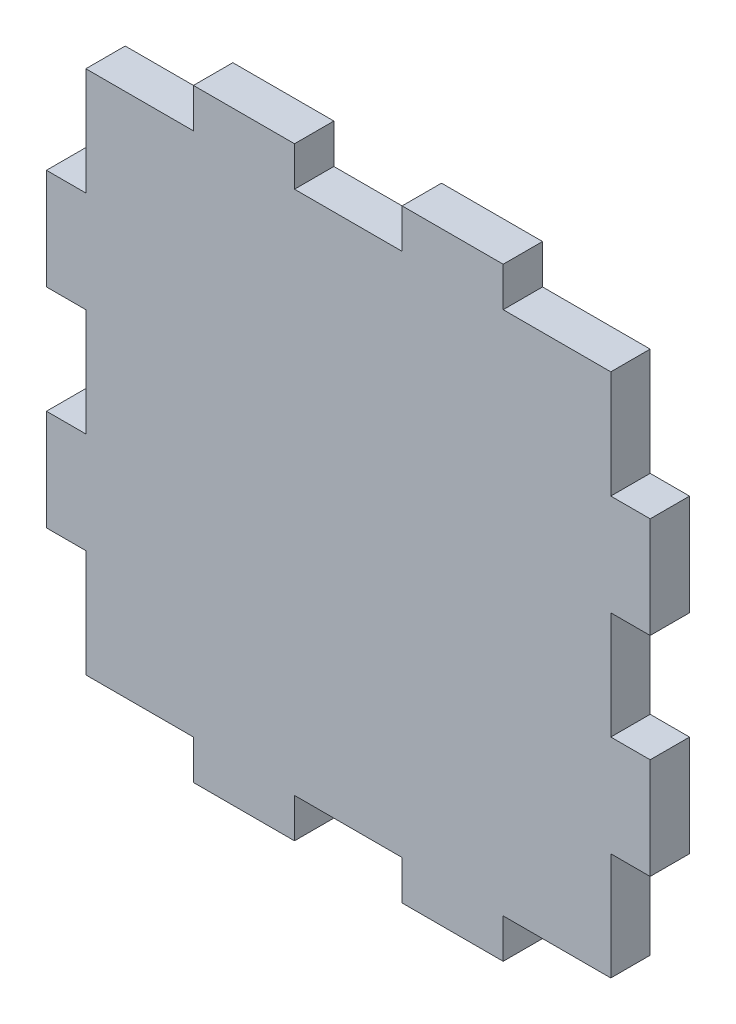
SolidWorks part; units mm, degrees
ref_plane "Alzado" through (0, 0, 0) normal (0, 0, 1) x (1, 0, 0)
ref_plane "Planta" through (0, 0, 0) normal (0, 1, 0) x (1, 0, 0)
ref_plane "Vista lateral" through (0, 0, 0) normal (1, 0, 0) x (0, 0, -1)
sketch "Croquis1" plane through (0, 0, 0) normal (0, 0, 1) x (1, 0, 0)
  line L0 (0, 0) -> (-14.3488, 0) construction
  line L1 (20, -20) -> (-20, -20)
  line L2 (20, -20) -> (20, 20)
  line L3 (20, 20) -> (-20, 20)
  line L4 (-20, -20) -> (-20, 20)
  line L5 (20, -20) -> (-20, 20) construction
  line L6 (20, 20) -> (-20, -20) construction
  line L7 (-11.8, 20) -> (-4.1, 20)
  line L8 (-11.8, 20) -> (-11.8, 23)
  line L9 (-11.8, 23) -> (-4.1, 23)
  line L10 (-4.1, 20) -> (-4.1, 23)
  line L11 (4.1, 20) -> (11.8, 20)
  line L12 (4.1, 20) -> (4.1, 23)
  line L13 (4.1, 23) -> (11.8, 23)
  line L14 (11.8, 20) -> (11.8, 23)
  line L15 (-20, 11.8) -> (-23, 11.8)
  line L16 (-20, 11.8) -> (-20, 4.1)
  line L17 (-20, 4.1) -> (-23, 4.1)
  line L18 (-23, 11.8) -> (-23, 4.1)
  line L19 (-20, -4.1) -> (-23, -4.1)
  line L20 (-20, -4.1) -> (-20, -11.8)
  line L21 (-20, -11.8) -> (-23, -11.8)
  line L22 (-23, -4.1) -> (-23, -11.8)
  line L23 (0, 0) -> (0, 14.3313) construction
  line L24 (20, -11.8) -> (23, -11.8)
  line L25 (23, -4.1) -> (23, -11.8)
  line L26 (20, -4.1) -> (23, -4.1)
  line L27 (20, -4.1) -> (20, -11.8)
  line L28 (20, 4.1) -> (23, 4.1)
  line L29 (23, 11.8) -> (23, 4.1)
  line L30 (20, 11.8) -> (23, 11.8)
  line L31 (20, 11.8) -> (20, 4.1)
  line L32 (4.1, -23) -> (11.8, -23)
  line L33 (11.8, -20) -> (11.8, -23)
  line L34 (4.1, -20) -> (11.8, -20)
  line L35 (4.1, -20) -> (4.1, -23)
  line L36 (-11.8, -23) -> (-4.1, -23)
  line L37 (-4.1, -20) -> (-4.1, -23)
  line L38 (-11.8, -20) -> (-4.1, -20)
  line L39 (-11.8, -20) -> (-11.8, -23)
  point P0 (0, 0)
  dimension "D1" = 40
  dimension "D2" = 40
  dimension "D3" = 8.2
  dimension "D4" = 8.2
  dimension "D5" = 8.2
  dimension "D6" = 7.7
  dimension "D7" = 3
  dimension "D8" = 3
  dimension "D9" = 3
  dimension "D10" = 3
  dimension "D11" = 8.2
  dimension "D12" = 8.2
  dimension "D13" = 8.2
  dimension "D14" = 7.7
extrude "Saliente-Extruir1" add sketch "Croquis1" along normal blind 3 contours L19 L22 L21 L4 | L1 L39 L36 L37 | L1 L35 L32 L33 | L26 L2 L24 L25 | L30 L2 L28 L29 | L15 L18 L17 L4 | L3 L10 L9 L8 | L3 L14 L13 L12 | L4 L1 L2 L3
